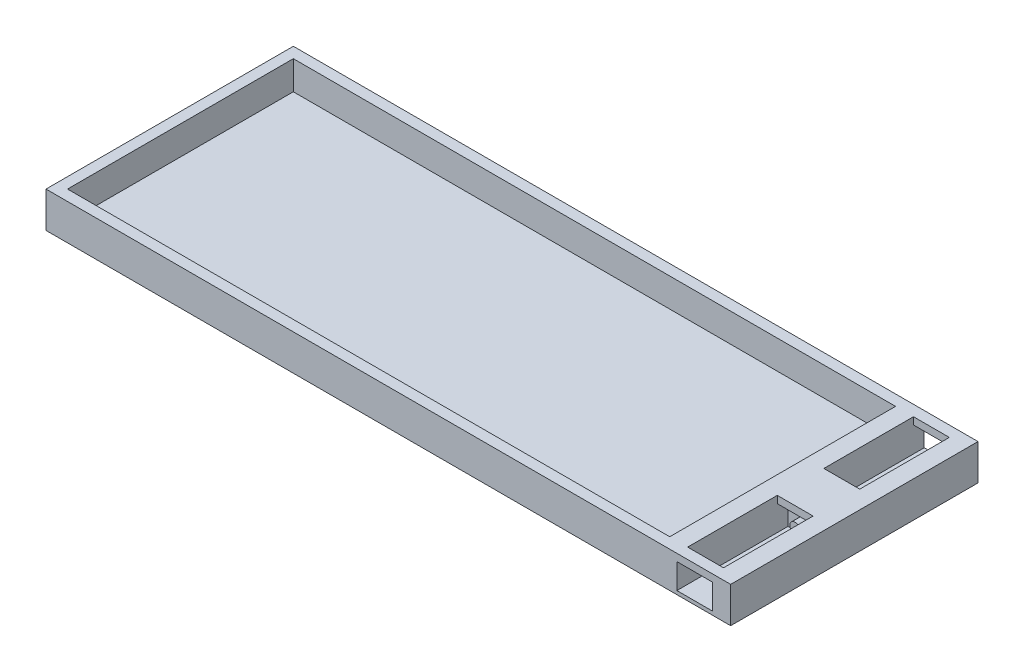
SolidWorks part; units mm, degrees
ref_plane "Front Plane" through (0, 0, 0) normal (0, 0, 1) x (1, 0, 0)
ref_plane "Top Plane" through (0, 0, 0) normal (0, 1, 0) x (1, 0, 0)
ref_plane "Right Plane" through (0, 0, 0) normal (1, 0, 0) x (0, 0, -1)
sketch "Sketch1" plane through (0, 0, 0) normal (0, 1, 0) x (1, 0, 0)
  line L0 (-84, 0) -> (-87, 0) construction
  line L1 (-84, -31.5) -> (84, -31.5)
  line L2 (-84, -31.5) -> (-84, 31.5)
  line L3 (-84, 31.5) -> (84, 31.5)
  line L4 (84, -31.5) -> (84, 31.5)
  line L5 (-84, -31.5) -> (84, 31.5) construction
  line L6 (-84, 31.5) -> (84, -31.5) construction
  line L7 (0, 31.5) -> (0, 34.5) construction
  line L8 (0, -31.5) -> (0, -34.5) construction
  line L9 (0, 34.5) -> (-87, 34.5)
  line L10 (-87, 34.5) -> (-87, -34.5)
  line L11 (-87, -34.5) -> (84, -34.5)
  line L12 (0, 34.5) -> (84, 34.5)
  line L13 (84, -34.5) -> (104, -34.5)
  line L14 (84, 34.5) -> (104, 34.5)
  line L15 (104, 34.5) -> (104, -34.5)
  point P0 (0, 0)
  dimension "D1" = 168
  dimension "D2" = 63
  dimension "D3" = 3
  dimension "D4" = 20
  dimension "D5" = 171
extrude "Boss-Extrude1" add sketch "Sketch1" along normal blind 10
sketch "Sketch2" plane through (0, 0, 0) normal (0, 1, 0) x (1, 0, 0)
  line L1 (-84, -31.5) -> (84, -31.5)
  line L2 (-84, -31.5) -> (-84, 31.5)
  line L3 (-84, 31.5) -> (84, 31.5)
  line L4 (84, -31.5) -> (84, 31.5)
  line L5 (-84, -31.5) -> (84, 31.5) construction
  line L6 (-84, 31.5) -> (84, -31.5) construction
  point P0 (0, 0)
extrude "Boss-Extrude2" add sketch "Sketch2" along normal blind 2
sketch "Sketch3" plane through (0, 10, 0) normal (0, 1, 0) x (1, 0, 0)
  line L0 (84, 31.5) -> (104, 31.5) construction
  line L1 (104, -34.5) -> (104, 34.5) construction
  line L2 (94, 31.5) -> (94, 6.5) construction
  line L3 (104, 0) -> (84, 0) construction
  line L4 (84, -31.5) -> (84, 31.5) construction
  line L5 (89, 6.5) -> (99, 6.5)
  line L6 (89, 6.5) -> (89, 31.5)
  line L7 (89, 31.5) -> (99, 31.5)
  line L8 (99, 31.5) -> (99, 6.5)
  point P14 (94, 6.5)
  dimension "D1" = 25
  dimension "D2" = 10
extrude "Cut-Extrude1" cut sketch "Sketch3" against normal through all
mirror "Mirror1" about plane through (0, 0, 0) normal (0, 0, 1) of "Cut-Extrude1"
sketch "Sketch4" plane through (0, 0, 6.5) normal (0, 0, 1) x (1, 0, 0)
  line L0 (89, 0) -> (99, 0)
  line L1 (89, 0) -> (99, 0) construction
  line L2 (94, 10) -> (94, 8) construction
  line L3 (89, 10) -> (99, 10) construction
  line L4 (99, 8) -> (89, 8)
  line L5 (89, 8) -> (89, 0)
  line L6 (99, 8) -> (99, 0)
  point P5 (94, 0)
  point P12 (94, 8)
  dimension "D1" = 10
  dimension "D2" = 2
  dimension "D3" = 8
extrude "Cut-Extrude2" cut sketch "Sketch4" against normal blind 3 and the other way up to next
mirror "Mirror2" about plane through (0, 0, 0) normal (0, 0, 1) of "Cut-Extrude2"
sketch "Sketch6" plane through (0, 0, 3.5) normal (0, 0, 1) x (1, 0, 0)
  line L0 (89, 0) -> (89, 1)
  line L1 (89, 8) -> (89, 0) construction
  line L2 (89, 1) -> (99, 1)
  line L3 (99, 8) -> (99, 0) construction
  line L4 (99, 1) -> (99, 0)
  line L5 (99, 0) -> (89, 0)
  dimension "D1" = 1
extrude "Boss-Extrude4" add sketch "Sketch6" along normal blind 31
mirror "Mirror5" about plane through (0, 0, 0) normal (0, 0, 1) of "Boss-Extrude4"
sketch "Sketch7" plane through (0, 0, 3.5) normal (0, 0, 1) x (1, 0, 0)
  line L0 (94, 8) -> (94, 1) construction
  line L1 (89, 8) -> (99, 8) construction
  line L2 (99, 1) -> (89, 1) construction
  circle A0 centre (94, 4.5) radius 1.5
  dimension "D1" = 3
extrude "Boss-Extrude5" add sketch "Sketch7" along normal blind 3
mirror "Mirror6" about plane through (0, 0, 0) normal (0, 0, 1) of "Boss-Extrude5"
sketch "Sketch8" plane through (-87, 0, 0) normal (-1, 0, 0) x (0, 0, 1)
  line L0 (5, 0) -> (-5, 0)
  line L1 (-34.5, 0) -> (34.5, 0) construction
  line L2 (-5, 0) -> (-5, 5)
  line L3 (-5, 5) -> (5, 5)
  line L4 (5, 5) -> (5, 0)
  point P6 (0, 0)
  dimension "D1" = 10
  dimension "D2" = 5
extrude "Boss-Extrude6" add sketch "Sketch8" along normal blind 3
